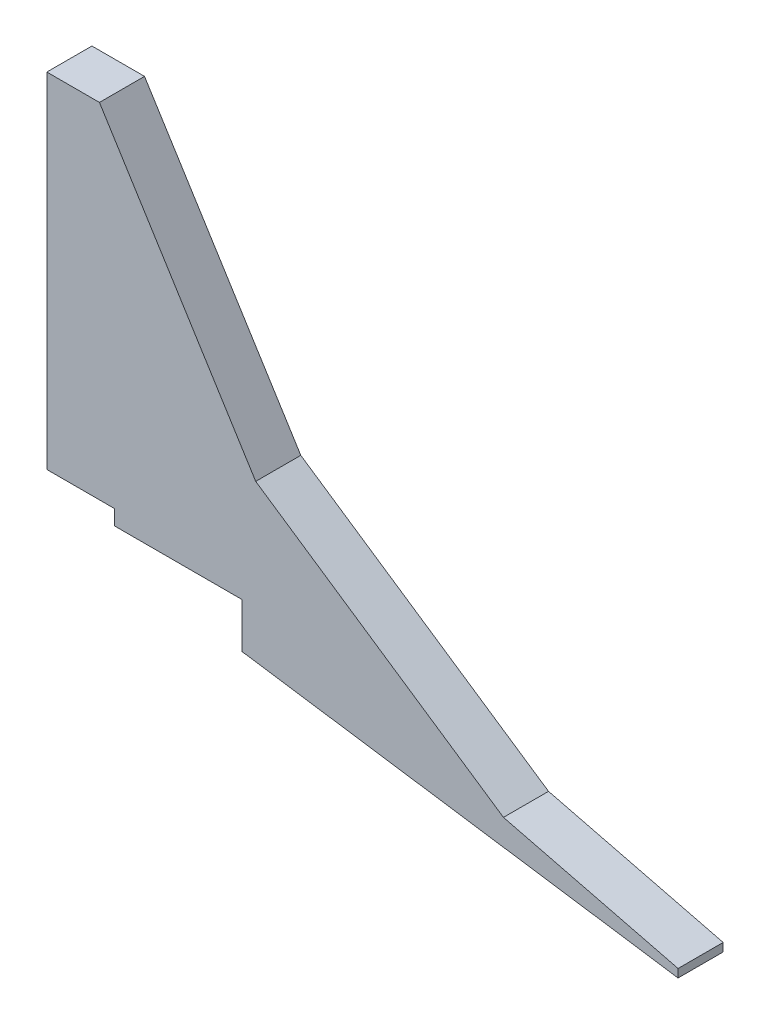
SolidWorks part; units mm, degrees
ref_plane "Front Plane" through (0, 0, 0) normal (0, 0, 1) x (1, 0, 0)
ref_plane "Top Plane" through (0, 0, 0) normal (0, 1, 0) x (1, 0, 0)
ref_plane "Right Plane" through (0, 0, 0) normal (1, 0, 0) x (0, 0, -1)
sketch "Seat against scoop and floor profile" plane through (0, 0, 0) normal (0, 0, 1) x (1, 0, 0)
  line L0 (94.5, 10) -> (103, 10)
  line L1 (103, 10) -> (103, 7)
  line L2 (103, 7) -> (132, 2.7)
  line L3 (132, 2.7) -> (132, 3.249)
  line L4 (132, 3.249) -> (120.3805, 6.1458)
  line L5 (120.3805, 6.1458) -> (103.8969, 17.2641)
  line L6 (103.8969, 17.2641) -> (93.5, 33.9026)
  line L7 (93.5, 33.9026) -> (90, 33.9026)
  line L8 (90, 33.9026) -> (90, 11)
  line L9 (90, 11) -> (94.5, 11)
  line L10 (94.5, 11) -> (94.5, 10)
extrude "Seat against scoop and floor" add sketch "Seat against scoop and floor profile" along normal blind 3
